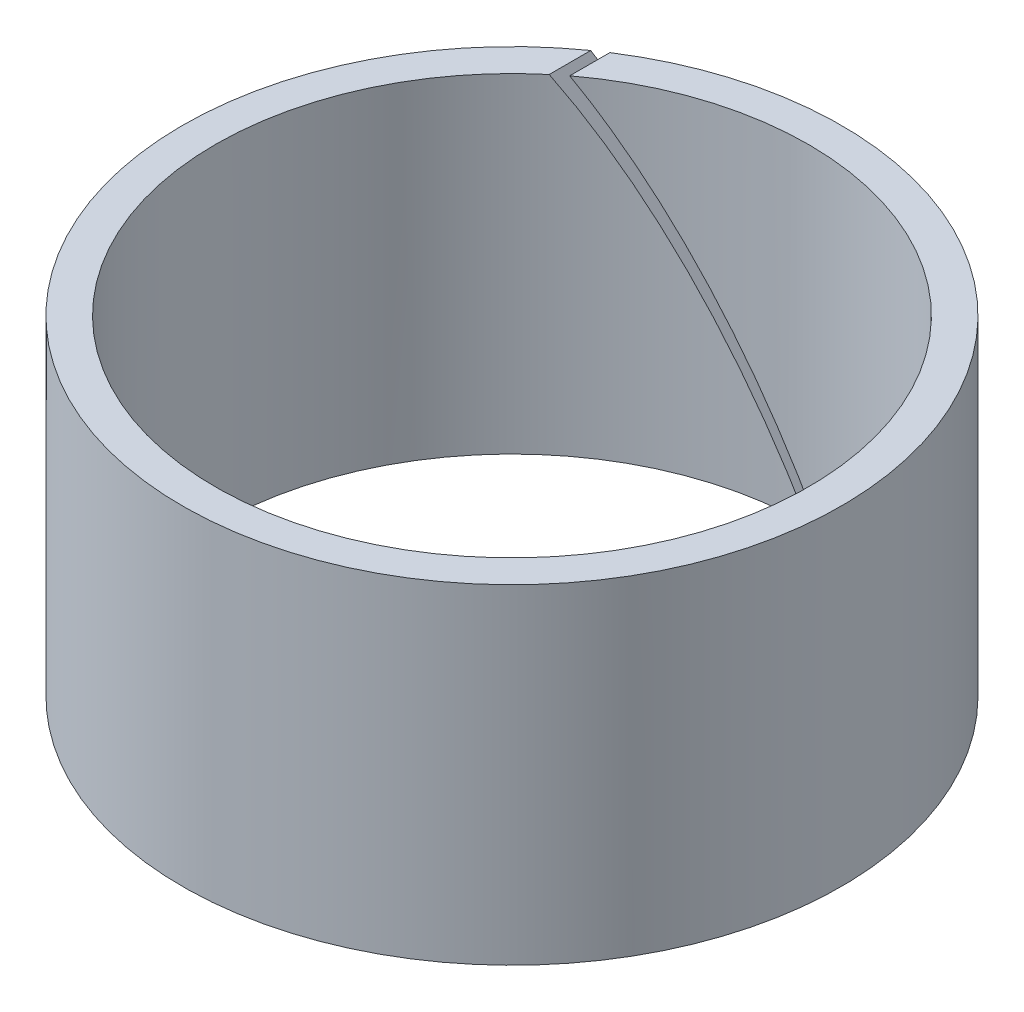
SolidWorks part; units mm, degrees
ref_plane "Front Plane" through (0, 0, 0) normal (0, 0, 1) x (1, 0, 0)
ref_plane "Top Plane" through (0, 0, 0) normal (0, 1, 0) x (1, 0, 0)
ref_plane "Right Plane" through (0, 0, 0) normal (1, 0, 0) x (0, 0, -1)
sketch "Sketch1" plane through (0, 0, 0) normal (0, 1, 0) x (1, 0, 0)
  circle A0 centre (0, 0) radius 10
  circle A1 centre (0, 0) radius 9
  dimension "D1" = 18
  dimension "D2" = 20
extrude "Boss-Extrude1" add sketch "Sketch1" along normal blind 10
sketch "Sketch3" plane through (0, 0, 0) normal (0, 0, 1) x (1, 0, 0)
  line L0 (0, 0) -> (0, 10) construction
  line L1 (10, 10) -> (-10, 10) construction
  line L2 (0, 0) -> (-5.7735, 10)
  line L3 (9, 10) -> (-9, 10) construction
  line L4 (0.3464, 0) -> (-5.4271, 10)
  line L5 (-10, 0) -> (10, 0) construction
  line L6 (-5.7735, 10) -> (-5.4271, 10)
  line L7 (0, 0) -> (0.3464, 0)
  dimension "D1" = 30
  dimension "D2" = 0.3
extrude "Cut-Extrude1" cut sketch "Sketch3" against normal up to next
